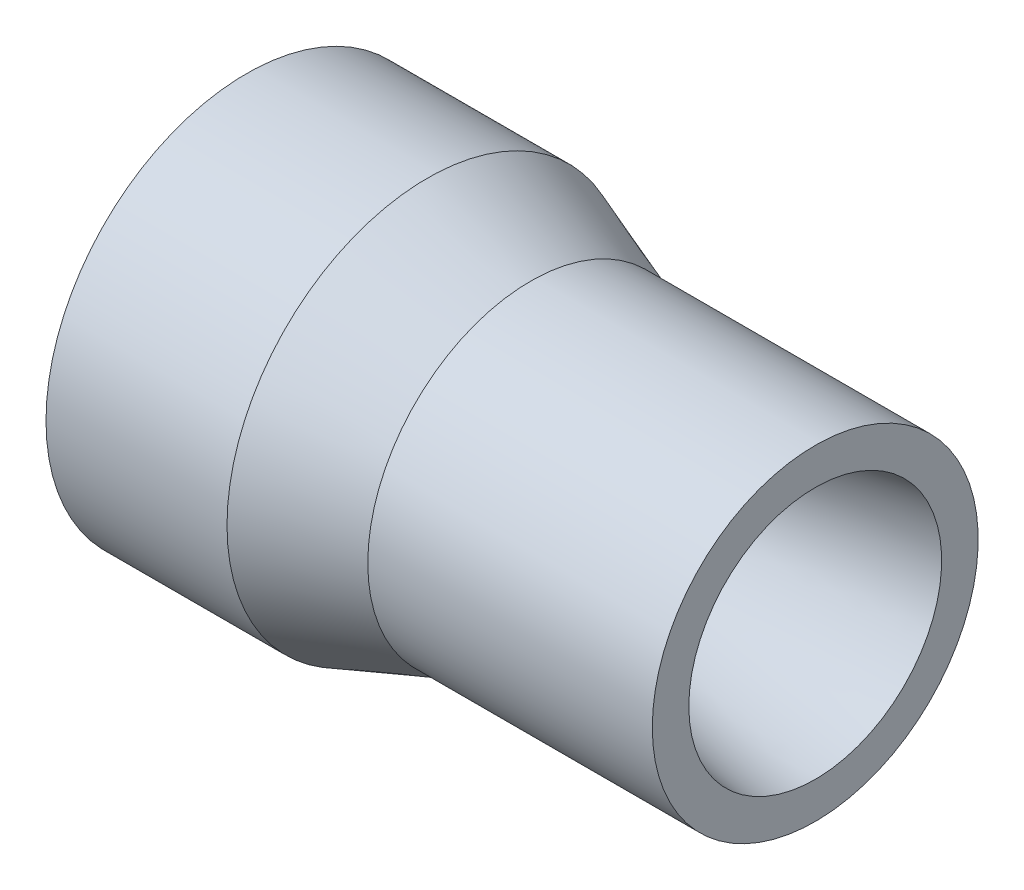
SolidWorks part; units mm, degrees
ref_plane "Front Plane" through (0, 0, 0) normal (0, 0, 1) x (1, 0, 0)
ref_plane "Top Plane" through (0, 0, 0) normal (0, 1, 0) x (1, 0, 0)
ref_plane "Right Plane" through (0, 0, 0) normal (1, 0, 0) x (0, 0, -1)
sketch "Sketch1" plane through (0, 0, 0) normal (0, 0, 1) x (1, 0, 0)
  line L0 (0, 0) -> (176.8872, 0) construction
  line L1 (0, 42.8625) -> (27.5254, 42.8625) construction
  line L2 (54.4274, 15.285) -> (96.5346, 15.285) construction
  line L3 (40.0098, 31.4386) -> (62.67, 18.3557)
  line L7 (0, 42.8625) -> (0, 52.2986)
  line L11 (76.0448, 15.6078) -> (93.9614, 21.826) construction
  line L13 (148.34, 32.975) -> (123.0603, 29.4222) construction
  line L14 (148.34, 32.975) -> (148.34, 42.5)
  line L15 (148.34, 42.5) -> (74.13, 42.5)
  line L17 (74.13, 42.5) -> (47.2086, 52.2986)
  line L18 (47.2086, 52.2986) -> (0, 52.2986)
  arc A0 (0, 42.8625) -> (40.0098, 31.4386) centre (-2.7952, -42.7019) cw
  arc A1 (74.13, 15.285) -> (62.67, 18.3557) centre (74.13, 38.205) cw
  arc A2 (74.13, 15.285) -> (76.0448, 15.6078) centre (74.13, 21.125) ccw
  spline S0 degree 3 poles (76.0448, 15.6078) (97.2352, 22.9623) (126.0123, 29.837) (148.34, 32.975) knots 0 0 0 0 1 1 1 1
  point P14 (132.2221, 30.7098)
  point P19 (123.0603, 29.4222)
  point P20 (0, 0)
  dimension "D4" = 22.92
  dimension "D5" = 74.13
  dimension "D7" = 5.84
  dimension "D11" = 52.2986
  dimension "D6" = 30
  dimension "D3" = 85.61
  dimension "D9" = 74.21
  dimension "D1" = 42.8625
  dimension "D2" = 15.285
  dimension "D8" = 19.14
  dimension "D10" = 32.975
  dimension "D12" = 8
  dimension "D13" = 9.525
  dimension "D14" = 20
revolve "Revolve1" add sketch "Sketch1" angle 360 about L0
